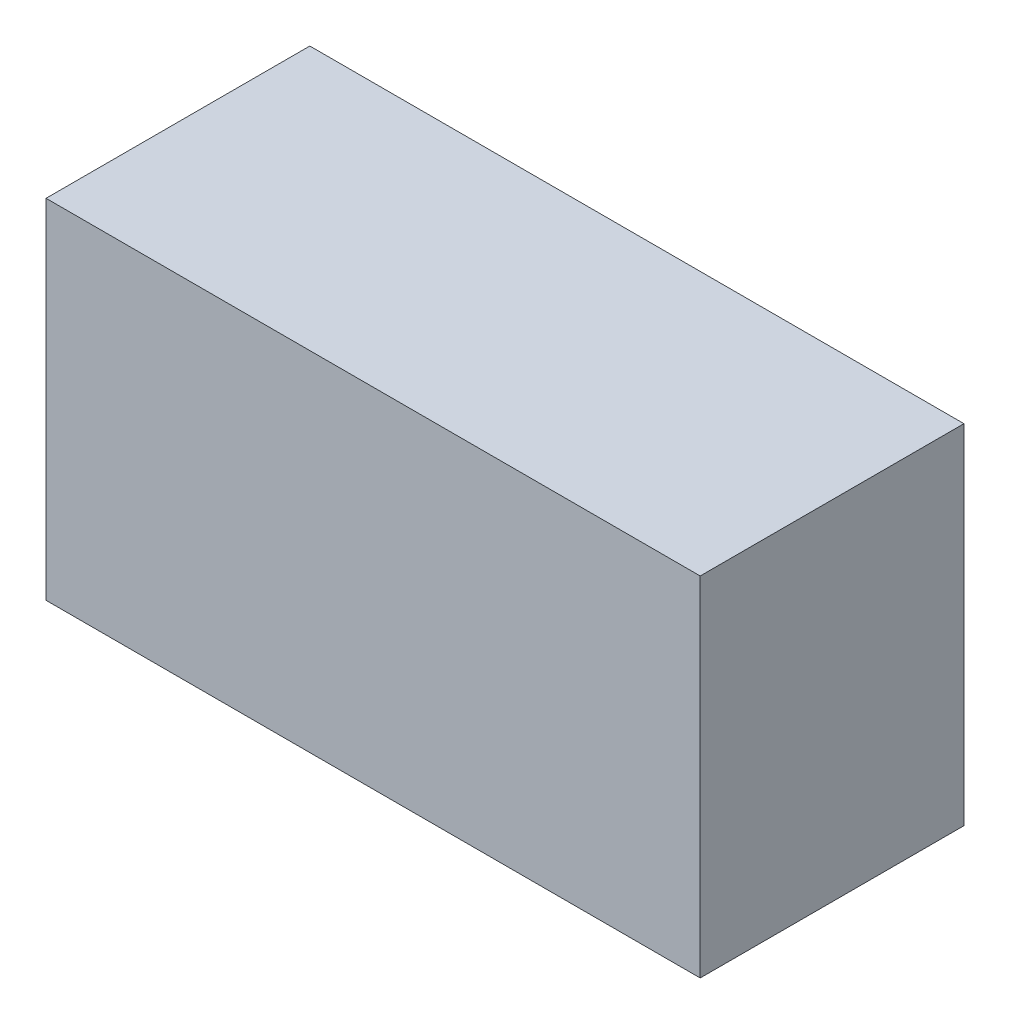
SolidWorks part; units mm, degrees
ref_plane "Front Plane" through (0, 0, 0) normal (0, 0, 1) x (1, 0, 0)
ref_plane "Top Plane" through (0, 0, 0) normal (0, 1, 0) x (1, 0, 0)
ref_plane "Right Plane" through (0, 0, 0) normal (1, 0, 0) x (0, 0, -1)
sketch "Sketch1" plane through (0, 0, 0) normal (0, 1, 0) x (1, 0, 0)
  line L1 (0, 25) -> (62, 25)
  line L2 (0, 25) -> (0, 0)
  line L3 (0, 0) -> (62, 0)
  line L4 (62, 25) -> (62, 0)
  point P4 (0, 0)
  dimension "D1" = 25
  dimension "D2" = 62
extrude "Boss-Extrude1" add sketch "Sketch1" along normal blind 33
